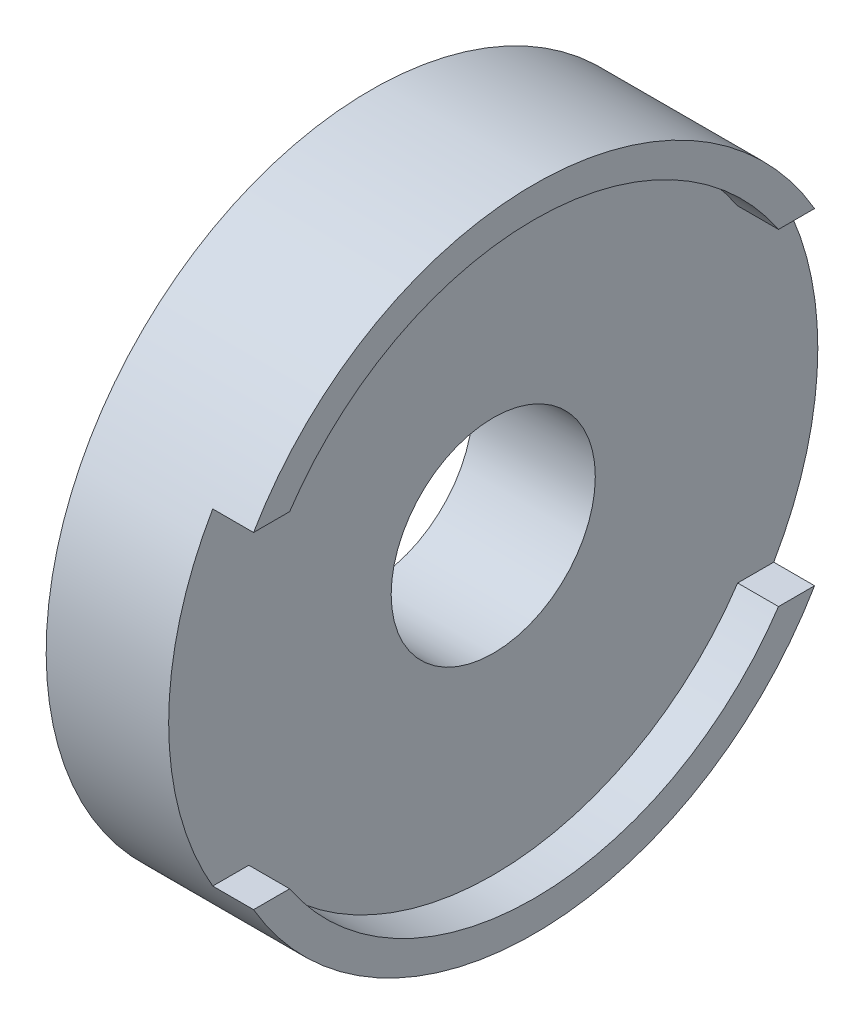
SolidWorks part; units mm, degrees
material "Plain Carbon Steel"
ref_plane "Front Plane" through (0, 0, 0) normal (0, 0, 1) x (1, 0, 0)
ref_plane "Top Plane" through (0, 0, 0) normal (0, 1, 0) x (1, 0, 0)
ref_plane "Right Plane" through (0, 0, 0) normal (1, 0, 0) x (0, 0, -1)
sketch "Sketch1" plane through (0, 0, 0) normal (1, 0, 0) x (0, 0, -1)
  circle A0 centre (0, 0) radius 15.9
  circle A1 centre (0, 0) radius 5
  dimension "D1" = 31.8
  dimension "D2" = 10
extrude "Boss-Extrude1" add sketch "Sketch1" along normal blind 6
sketch "Sketch2" plane through (6, 0, 0) normal (1, 0, 0) x (0, 0, -1)
  line L0 (11.9733, -8) -> (13.7408, -8)
  line L1 (-13.7408, -8) -> (-11.9733, -8)
  line L2 (-13.7408, 8) -> (-11.9733, 8)
  line L4 (11.9733, 8) -> (13.7408, 8)
  arc A0 (-11.9733, -8) -> (11.9733, -8) centre (0, 0) ccw
  circle A1 centre (0, 0) radius 15.9
  arc A2 (-13.7408, -8) -> (13.7408, -8) centre (0, 0) ccw
  circle A3 centre (0, 0) radius 15.9 construction
  circle A4 centre (0, 0) radius 14.4 construction
  arc A5 (13.7408, 8) -> (-13.7408, 8) centre (0, 0) ccw
  arc A6 (11.9733, 8) -> (-11.9733, 8) centre (0, 0) ccw
  dimension "D1" = 0
  dimension "D2" = 1.5
extrude "Boss-Extrude2" add sketch "Sketch2" along normal blind 2
